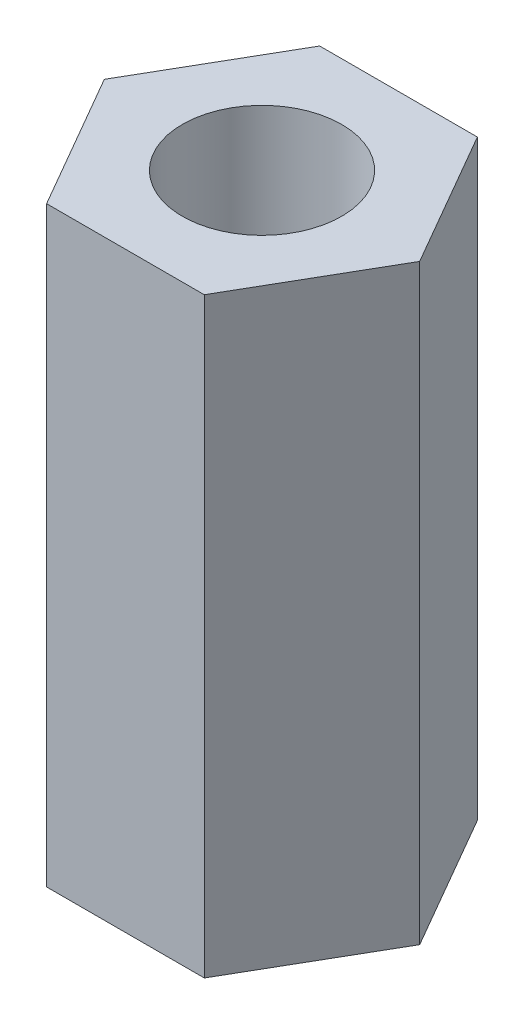
SolidWorks part; units mm, degrees
ref_plane "Plan de face" through (0, 0, 0) normal (0, 0, 1) x (1, 0, 0)
ref_plane "Plan de dessus" through (0, 0, 0) normal (0, 1, 0) x (1, 0, 0)
ref_plane "Plan de droite" through (0, 0, 0) normal (1, 0, 0) x (0, 0, -1)
sketch "Esquisse1" plane through (0, 0, 0) normal (0, 1, 0) x (1, 0, 0)
  line L1 (3.4641, 0) -> (1.7321, 3)
  line L2 (1.7321, 3) -> (-1.7321, 3)
  line L3 (-1.7321, 3) -> (-3.4641, 0)
  line L4 (-3.4641, 0) -> (-1.7321, -3)
  line L5 (-1.7321, -3) -> (1.7321, -3)
  line L6 (1.7321, -3) -> (3.4641, 0)
  circle A0 centre (0, 0) radius 1.75
  circle A1 centre (0, 0) radius 3 construction
  dimension "D1" = 3.5
  dimension "D2" = 6
extrude "Boss.-Extru.1" add sketch "Esquisse1" along normal blind 13
